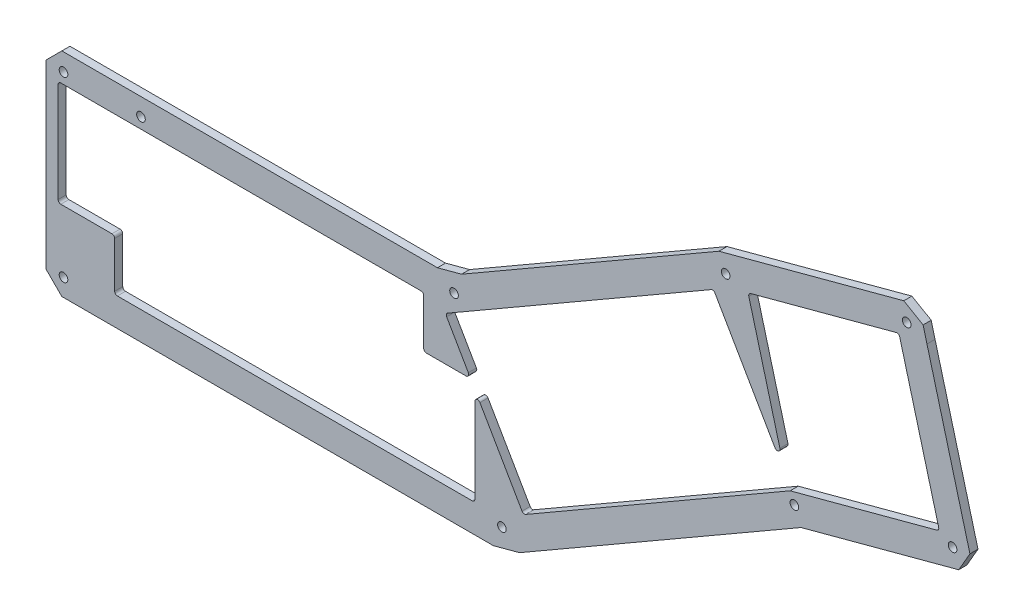
SolidWorks part; units mm, degrees
ref_plane "Plan de face" through (0, 0, 0) normal (0, 0, 1) x (1, 0, 0)
ref_plane "Plan de dessus" through (0, 0, 0) normal (0, 1, 0) x (1, 0, 0)
ref_plane "Plan de droite" through (0, 0, 0) normal (1, 0, 0) x (0, 0, -1)
sketch "Esquisse1" plane through (0, 0, 0) normal (0, 0, 1) x (1, 0, 0)
  line L0 (-73.9886, 18.0851) -> (-59.9886, 18.0851) construction
  line L1 (-73.9886, 37.0851) -> (-59.9886, 37.0851) construction
  line L2 (-73.9886, 37.0851) -> (-73.9886, 23.0851) construction
  line L3 (-73.9886, 23.0851) -> (-59.9886, 23.0851) construction
  line L4 (-59.9886, 37.0851) -> (-59.9886, 23.0851) construction
  line L5 (-73.9886, 18.0851) -> (-73.9886, 4.0851) construction
  line L6 (-73.9886, 4.0851) -> (-59.9886, 4.0851) construction
  line L7 (-59.9886, 18.0851) -> (-59.9886, 4.0851) construction
  line L8 (-73.9886, -0.9149) -> (-59.9886, -0.9149) construction
  line L9 (-73.9886, -0.9149) -> (-73.9886, -14.9149) construction
  line L10 (-73.9886, -14.9149) -> (-59.9886, -14.9149) construction
  line L11 (-59.9886, -0.9149) -> (-59.9886, -14.9149) construction
  line L12 (-73.9886, 37.0851) -> (-73.9886, 18.0851) construction
  line L13 (-54.9886, 18.0851) -> (-40.9886, 18.0851) construction
  line L14 (-54.9886, 37.0851) -> (-40.9886, 37.0851) construction
  line L15 (-54.9886, 37.0851) -> (-54.9886, 23.0851) construction
  line L16 (-54.9886, 23.0851) -> (-40.9886, 23.0851) construction
  line L17 (-40.9886, 37.0851) -> (-40.9886, 23.0851) construction
  line L18 (-54.9886, 18.0851) -> (-54.9886, 4.0851) construction
  line L19 (-54.9886, 4.0851) -> (-40.9886, 4.0851) construction
  line L20 (-40.9886, 18.0851) -> (-40.9886, 4.0851) construction
  line L21 (-54.9886, -0.9149) -> (-40.9886, -0.9149) construction
  line L22 (-54.9886, -0.9149) -> (-54.9886, -14.9149) construction
  line L23 (-54.9886, -14.9149) -> (-40.9886, -14.9149) construction
  line L24 (-40.9886, -0.9149) -> (-40.9886, -14.9149) construction
  line L25 (-54.9886, 37.0851) -> (-54.9886, 18.0851) construction
  line L26 (-35.9886, 18.0851) -> (-21.9886, 18.0851) construction
  line L27 (-35.9886, 37.0851) -> (-21.9886, 37.0851) construction
  line L28 (-35.9886, 37.0851) -> (-35.9886, 23.0851) construction
  line L29 (-35.9886, 23.0851) -> (-21.9886, 23.0851) construction
  line L30 (-21.9886, 37.0851) -> (-21.9886, 23.0851) construction
  line L31 (-35.9886, 18.0851) -> (-35.9886, 4.0851) construction
  line L32 (-35.9886, 4.0851) -> (-21.9886, 4.0851) construction
  line L33 (-21.9886, 18.0851) -> (-21.9886, 4.0851) construction
  line L34 (-35.9886, -0.9149) -> (-21.9886, -0.9149) construction
  line L35 (-35.9886, -0.9149) -> (-35.9886, -14.9149) construction
  line L36 (-35.9886, -14.9149) -> (-21.9886, -14.9149) construction
  line L37 (-21.9886, -0.9149) -> (-21.9886, -14.9149) construction
  line L38 (-35.9886, 37.0851) -> (-35.9886, 18.0851) construction
  line L39 (-16.9886, 18.0851) -> (-2.9886, 18.0851) construction
  line L40 (-16.9886, 37.0851) -> (-2.9886, 37.0851) construction
  line L41 (-16.9886, 37.0851) -> (-16.9886, 23.0851) construction
  line L42 (-16.9886, 23.0851) -> (-2.9886, 23.0851) construction
  line L43 (-2.9886, 37.0851) -> (-2.9886, 23.0851) construction
  line L44 (-16.9886, 18.0851) -> (-16.9886, 4.0851) construction
  line L45 (-16.9886, 4.0851) -> (-2.9886, 4.0851) construction
  line L46 (-2.9886, 18.0851) -> (-2.9886, 4.0851) construction
  line L47 (-16.9886, -0.9149) -> (-2.9886, -0.9149) construction
  line L48 (-16.9886, -0.9149) -> (-16.9886, -14.9149) construction
  line L49 (-16.9886, -14.9149) -> (-2.9886, -14.9149) construction
  line L50 (-2.9886, -0.9149) -> (-2.9886, -14.9149) construction
  line L51 (-16.9886, 37.0851) -> (-16.9886, 18.0851) construction
  line L52 (2.0114, 18.0851) -> (16.0114, 18.0851) construction
  line L53 (2.0114, 37.0851) -> (16.0114, 37.0851) construction
  line L54 (2.0114, 37.0851) -> (2.0114, 23.0851) construction
  line L55 (2.0114, 23.0851) -> (16.0114, 23.0851) construction
  line L56 (16.0114, 37.0851) -> (16.0114, 23.0851) construction
  line L57 (2.0114, 18.0851) -> (2.0114, 4.0851) construction
  line L58 (2.0114, 4.0851) -> (16.0114, 4.0851) construction
  line L59 (16.0114, 18.0851) -> (16.0114, 4.0851) construction
  line L60 (2.0114, -0.9149) -> (16.0114, -0.9149) construction
  line L61 (2.0114, -0.9149) -> (2.0114, -14.9149) construction
  line L62 (2.0114, -14.9149) -> (16.0114, -14.9149) construction
  line L63 (16.0114, -0.9149) -> (16.0114, -14.9149) construction
  line L64 (2.0114, 37.0851) -> (2.0114, 18.0851) construction
  line L65 (21.0114, 18.0851) -> (35.0114, 18.0851) construction
  line L66 (21.0114, 37.0851) -> (35.0114, 37.0851) construction
  line L67 (21.0114, 37.0851) -> (21.0114, 23.0851) construction
  line L68 (21.0114, 23.0851) -> (35.0114, 23.0851) construction
  line L69 (35.0114, 37.0851) -> (35.0114, 23.0851) construction
  line L70 (21.0114, 18.0851) -> (21.0114, 4.0851) construction
  line L71 (21.0114, 4.0851) -> (35.0114, 4.0851) construction
  line L72 (35.0114, 18.0851) -> (35.0114, 4.0851) construction
  line L73 (21.0114, -0.9149) -> (35.0114, -0.9149) construction
  line L74 (21.0114, -0.9149) -> (21.0114, -14.9149) construction
  line L75 (21.0114, -14.9149) -> (35.0114, -14.9149) construction
  line L76 (35.0114, -0.9149) -> (35.0114, -14.9149) construction
  line L77 (21.0114, 37.0851) -> (21.0114, 18.0851) construction
  line L78 (40.0114, 18.0851) -> (54.0114, 18.0851) construction
  line L79 (-97.7538, 39.0851) -> (-97.7538, 2.0851)
  line L80 (-97.7538, 39.0851) -> (-97.7538, 1.0851) construction
  line L81 (-76.7538, 0.0851) -> (-76.7538, -16.9149)
  line L82 (-95.7538, 44.0851) -> (-53.0442, 44.0851) construction
  line L83 (40.0114, 18.0851) -> (40.0114, 4.0851) construction
  line L84 (40.0114, 4.0851) -> (54.0114, 4.0851) construction
  line L85 (54.0114, 18.0851) -> (54.0114, 4.0851) construction
  line L86 (40.0114, -0.9149) -> (54.0114, -0.9149) construction
  line L87 (40.0114, -0.9149) -> (40.0114, -14.9149) construction
  line L88 (40.0114, -14.9149) -> (54.0114, -14.9149) construction
  line L89 (54.0114, -0.9149) -> (54.0114, -14.9149) construction
  line L90 (40.0114, 20.0851) -> (40.0114, 18.0851) construction
  line L91 (-73.9886, 18.0851) -> (-54.9886, 18.0851) construction
  line L92 (56.0114, 20.0851) -> (56.7532, 18.8002) construction
  line L93 (-66.9886, 37.0851) -> (-66.9886, 44.0851) construction
  line L94 (67.3933, 2.371) -> (74.3933, -9.7534) construction
  line L95 (146.1202, 94.012) -> (168.4398, 55.3534)
  line L96 (158.7183, 99.2303) -> (170.2717, 56.1122)
  line L97 (19.0114, 39.0851) -> (37.0114, 39.0851) construction
  line L98 (37.0114, 39.0851) -> (37.0114, 21.0851) construction
  line L99 (19.0114, 21.0851) -> (37.0114, 21.0851) construction
  line L100 (19.0114, 39.0851) -> (19.0114, 21.0851) construction
  line L101 (79.4363, 55.512) -> (88.4363, 39.9235) construction
  line L102 (88.4363, 39.9235) -> (72.8478, 30.9235) construction
  line L103 (63.8478, 46.512) -> (72.8478, 30.9235) construction
  line L104 (79.4363, 55.512) -> (63.8478, 46.512) construction
  line L105 (62.9818, 46.012) -> (71.9818, 30.4235) construction
  line L106 (71.9818, 30.4235) -> (56.3933, 21.4235) construction
  line L107 (47.3933, 37.012) -> (56.3933, 21.4235) construction
  line L108 (62.9818, 46.012) -> (47.3933, 37.012) construction
  line L109 (164.2542, 60.603) -> (148.6657, 51.603) construction
  line L110 (62.2497, 43.2799) -> (71.7497, 26.8254) construction
  line L111 (78.7042, 52.7799) -> (88.2042, 36.3254) construction
  line L112 (95.1587, 62.2799) -> (104.6587, 45.8254) construction
  line L113 (111.6132, 71.7799) -> (121.1132, 55.3254) construction
  line L114 (128.0677, 81.2799) -> (137.5677, 64.8254) construction
  line L115 (144.5221, 90.7799) -> (154.0221, 74.3254) construction
  line L116 (148.6657, 51.603) -> (157.6657, 36.0146) construction
  line L117 (69.1254, 3.371) -> (76.1254, -8.7534) construction
  line L118 (88.2497, -1.7534) -> (76.1254, -8.7534) construction
  line L119 (81.2497, 10.371) -> (88.2497, -1.7534) construction
  line L120 (81.2497, 10.371) -> (69.1254, 3.371) construction
  line L121 (59.6254, 19.8254) -> (66.6254, 7.7011) construction
  line L122 (78.7497, 14.7011) -> (66.6254, 7.7011) construction
  line L123 (71.7497, 26.8254) -> (78.7497, 14.7011) construction
  line L124 (50.1254, 36.2799) -> (57.1254, 24.1556) construction
  line L125 (69.2497, 31.1556) -> (57.1254, 24.1556) construction
  line L126 (62.2497, 43.2799) -> (69.2497, 31.1556) construction
  line L127 (62.2497, 43.2799) -> (50.1254, 36.2799) construction
  line L128 (71.7497, 26.8254) -> (59.6254, 19.8254) construction
  line L129 (85.5799, 12.871) -> (92.5799, 0.7466) construction
  line L130 (104.7042, 7.7466) -> (92.5799, 0.7466) construction
  line L131 (97.7042, 19.871) -> (104.7042, 7.7466) construction
  line L132 (97.7042, 19.871) -> (85.5799, 12.871) construction
  line L133 (76.0799, 29.3254) -> (83.0799, 17.2011) construction
  line L134 (95.2042, 24.2011) -> (83.0799, 17.2011) construction
  line L135 (88.2042, 36.3254) -> (95.2042, 24.2011) construction
  line L136 (66.5799, 45.7799) -> (73.5799, 33.6556) construction
  line L137 (85.7042, 40.6556) -> (73.5799, 33.6556) construction
  line L138 (78.7042, 52.7799) -> (85.7042, 40.6556) construction
  line L139 (78.7042, 52.7799) -> (66.5799, 45.7799) construction
  line L140 (88.2042, 36.3254) -> (76.0799, 29.3254) construction
  line L141 (102.0343, 22.371) -> (109.0343, 10.2466) construction
  line L142 (121.1587, 17.2466) -> (109.0343, 10.2466) construction
  line L143 (114.1587, 29.371) -> (121.1587, 17.2466) construction
  line L144 (114.1587, 29.371) -> (102.0343, 22.371) construction
  line L145 (92.5343, 38.8254) -> (99.5343, 26.7011) construction
  line L146 (111.6587, 33.7011) -> (99.5343, 26.7011) construction
  line L147 (104.6587, 45.8254) -> (111.6587, 33.7011) construction
  line L148 (83.0343, 55.2799) -> (90.0343, 43.1556) construction
  line L149 (102.1587, 50.1556) -> (90.0343, 43.1556) construction
  line L150 (95.1587, 62.2799) -> (102.1587, 50.1556) construction
  line L151 (95.1587, 62.2799) -> (83.0343, 55.2799) construction
  line L152 (104.6587, 45.8254) -> (92.5343, 38.8254) construction
  line L153 (118.4888, 31.871) -> (125.4888, 19.7466) construction
  line L154 (137.6132, 26.7466) -> (125.4888, 19.7466) construction
  line L155 (130.6132, 38.871) -> (137.6132, 26.7466) construction
  line L156 (130.6132, 38.871) -> (118.4888, 31.871) construction
  line L157 (108.9888, 48.3254) -> (115.9888, 36.2011) construction
  line L158 (128.1132, 43.2011) -> (115.9888, 36.2011) construction
  line L159 (121.1132, 55.3254) -> (128.1132, 43.2011) construction
  line L160 (99.4888, 64.7799) -> (106.4888, 52.6556) construction
  line L161 (118.6132, 59.6556) -> (106.4888, 52.6556) construction
  line L162 (111.6132, 71.7799) -> (118.6132, 59.6556) construction
  line L163 (111.6132, 71.7799) -> (99.4888, 64.7799) construction
  line L164 (121.1132, 55.3254) -> (108.9888, 48.3254) construction
  line L165 (134.9433, 41.371) -> (141.9433, 29.2466) construction
  line L166 (154.0677, 36.2466) -> (141.9433, 29.2466) construction
  line L167 (147.0677, 48.371) -> (154.0677, 36.2466) construction
  line L168 (147.0677, 48.371) -> (134.9433, 41.371) construction
  line L169 (125.4433, 57.8254) -> (132.4433, 45.7011) construction
  line L170 (144.5677, 52.7011) -> (132.4433, 45.7011) construction
  line L171 (137.5677, 64.8254) -> (144.5677, 52.7011) construction
  line L172 (115.9433, 74.2799) -> (122.9433, 62.1556) construction
  line L173 (135.0677, 69.1556) -> (122.9433, 62.1556) construction
  line L174 (128.0677, 81.2799) -> (135.0677, 69.1556) construction
  line L175 (128.0677, 81.2799) -> (115.9433, 74.2799) construction
  line L176 (137.5677, 64.8254) -> (125.4433, 57.8254) construction
  line L177 (151.3978, 50.871) -> (158.3978, 38.7466) construction
  line L178 (170.5221, 45.7466) -> (158.3978, 38.7466) construction
  line L179 (163.5221, 57.871) -> (170.5221, 45.7466) construction
  line L180 (163.5221, 57.871) -> (151.3978, 50.871) construction
  line L181 (141.8978, 67.3254) -> (148.8978, 55.2011) construction
  line L182 (161.0221, 62.2011) -> (148.8978, 55.2011) construction
  line L183 (154.0221, 74.3254) -> (161.0221, 62.2011) construction
  line L184 (132.3978, 83.7799) -> (139.3978, 71.6556) construction
  line L185 (151.5221, 78.6556) -> (139.3978, 71.6556) construction
  line L186 (144.5221, 90.7799) -> (151.5221, 78.6556) construction
  line L187 (144.5221, 90.7799) -> (132.3978, 83.7799) construction
  line L188 (154.0221, 74.3254) -> (141.8978, 67.3254) construction
  line L189 (173.2542, 45.0146) -> (157.6657, 36.0146) construction
  line L190 (164.2542, 60.603) -> (173.2542, 45.0146) construction
  line L191 (178.3169, 34.0986) -> (169.0534, 56.4627) construction
  line L192 (169.5193, 62.7839) -> (174.1781, 45.3972) construction
  line L193 (174.1781, 45.3972) -> (191.5647, 50.056) construction
  line L194 (186.906, 67.4426) -> (191.5647, 50.056) construction
  line L195 (162.1337, 98.0749) -> (167.0513, 79.7223) construction
  line L196 (169.5193, 62.7839) -> (186.906, 67.4426) construction
  line L197 (167.0513, 79.7223) -> (180.5742, 83.3457) construction
  line L198 (162.1337, 98.0749) -> (175.6567, 101.6983) construction
  line L199 (162.1337, 98.0749) -> (165.7572, 84.5519) construction
  line L200 (165.7572, 84.5519) -> (179.2801, 88.1754) construction
  line L201 (175.6567, 101.6983) -> (179.2801, 88.1754) construction
  line L202 (167.0513, 79.7223) -> (170.6747, 66.1993) construction
  line L203 (170.6747, 66.1993) -> (184.1977, 69.8228) construction
  line L204 (180.5742, 83.3457) -> (184.1977, 69.8228) construction
  line L205 (171.9688, 61.3697) -> (185.4918, 64.9932) construction
  line L206 (171.9688, 61.3697) -> (175.5923, 47.8467) construction
  line L207 (175.5923, 47.8467) -> (189.1152, 51.4702) construction
  line L208 (185.4918, 64.9932) -> (189.1152, 51.4702) construction
  line L209 (185.4038, 84.6398) -> (198.9268, 88.2633) construction
  line L210 (180.4863, 102.9924) -> (194.0092, 106.6159) construction
  line L211 (180.4863, 102.9924) -> (184.1097, 89.4695) construction
  line L212 (184.1097, 89.4695) -> (197.6327, 93.0929) construction
  line L213 (194.0092, 106.6159) -> (197.6327, 93.0929) construction
  line L214 (185.4038, 84.6398) -> (189.0273, 71.1169) construction
  line L215 (189.0273, 71.1169) -> (202.5503, 74.7403) construction
  line L216 (198.9268, 88.2633) -> (202.5503, 74.7403) construction
  line L217 (190.3214, 66.2873) -> (203.8444, 69.9107) construction
  line L218 (190.3214, 66.2873) -> (193.9449, 52.7643) construction
  line L219 (193.9449, 52.7643) -> (207.4678, 56.3878) construction
  line L220 (203.8444, 69.9107) -> (207.4678, 56.3878) construction
  line L221 (187.8719, 67.7015) -> (192.5307, 50.3148) construction
  line L222 (192.5307, 50.3148) -> (209.9173, 54.9735) construction
  line L223 (205.2586, 72.3602) -> (209.9173, 54.9735) construction
  line L224 (180.4863, 102.9924) -> (185.4038, 84.6398) construction
  line L225 (187.8719, 67.7015) -> (205.2586, 72.3602) construction
  line L226 (203.7564, 89.5574) -> (217.2794, 93.1809) construction
  line L227 (198.8389, 107.91) -> (212.3618, 111.5335) construction
  line L228 (198.8389, 107.91) -> (202.4623, 94.387) construction
  line L229 (202.4623, 94.387) -> (215.9853, 98.0105) construction
  line L230 (212.3618, 111.5335) -> (215.9853, 98.0105) construction
  line L231 (203.7564, 89.5574) -> (207.3799, 76.0344) construction
  line L232 (207.3799, 76.0344) -> (220.9029, 79.6579) construction
  line L233 (217.2794, 93.1809) -> (220.9029, 79.6579) construction
  line L234 (208.674, 71.2048) -> (222.197, 74.8283) construction
  line L235 (208.674, 71.2048) -> (212.2975, 57.6819) construction
  line L236 (212.2975, 57.6819) -> (225.8204, 61.3053) construction
  line L237 (222.197, 74.8283) -> (225.8204, 61.3053) construction
  line L238 (206.2245, 72.619) -> (210.8833, 55.2324) construction
  line L239 (210.8833, 55.2324) -> (228.2699, 59.8911) construction
  line L240 (223.6112, 77.2778) -> (228.2699, 59.8911) construction
  line L241 (198.8389, 107.91) -> (203.7564, 89.5574) construction
  line L242 (206.2245, 72.619) -> (223.6112, 77.2778) construction
  line L243 (167.0513, 79.7223) -> (185.4038, 84.6398) construction
  line L244 (38.0114, 20.0851) -> (56.0114, 20.0851) construction
  line L245 (56.0114, 20.0851) -> (56.0114, 2.0851) construction
  line L246 (38.0114, 2.0851) -> (56.0114, 2.0851) construction
  line L247 (38.0114, 20.0851) -> (38.0114, 2.0851) construction
  line L248 (72.4818, 29.5575) -> (56.8933, 20.5575) construction
  line L249 (56.8933, 20.5575) -> (65.8933, 4.969) construction
  line L250 (81.4818, 13.969) -> (65.8933, 4.969) construction
  line L251 (72.4818, 29.5575) -> (81.4818, 13.969) construction
  line L252 (56.8933, 20.5575) -> (57.6111, 19.3142) construction
  line L253 (164.6018, 81.1365) -> (169.2605, 63.7498) construction
  line L254 (169.2605, 63.7498) -> (186.6472, 68.4086) construction
  line L255 (181.9884, 85.7952) -> (186.6472, 68.4086) construction
  line L256 (164.6018, 81.1365) -> (181.9884, 85.7952) construction
  line L257 (154.7542, 77.0575) -> (163.7542, 61.469) construction
  line L258 (163.7542, 61.469) -> (148.1657, 52.469) construction
  line L259 (139.1657, 68.0575) -> (148.1657, 52.469) construction
  line L260 (154.7542, 77.0575) -> (139.1657, 68.0575) construction
  line L261 (196.3894, 109.3242) -> (213.776, 113.983) construction
  line L262 (-94.7538, 35.7952) -> (-76.7538, 35.7952) construction
  line L263 (-94.7538, 35.7952) -> (-94.7538, 2.7952) construction
  line L264 (-94.7538, 2.7952) -> (-76.7538, 2.7952) construction
  line L265 (-76.7538, 35.7952) -> (-76.7538, 2.7952) construction
  line L266 (213.776, 113.983) -> (218.4348, 96.5963) construction
  line L267 (201.0481, 91.9375) -> (218.4348, 96.5963) construction
  line L268 (196.3894, 109.3242) -> (201.0481, 91.9375) construction
  line L269 (-75.9886, -16.9149) -> (-57.9886, -16.9149) construction
  line L270 (-57.9886, 1.0851) -> (-57.9886, -16.9149) construction
  line L271 (-75.9886, 1.0851) -> (-57.9886, 1.0851) construction
  line L272 (-75.9886, 1.0851) -> (-75.9886, -16.9149) construction
  line L273 (38.0114, -16.9149) -> (56.0114, -16.9149) construction
  line L274 (56.0114, 1.0851) -> (56.0114, -16.9149) construction
  line L275 (38.0114, 1.0851) -> (56.0114, 1.0851) construction
  line L276 (38.0114, 1.0851) -> (38.0114, -16.9149) construction
  line L277 (-75.9886, 39.0851) -> (-57.9886, 39.0851) construction
  line L278 (-57.9886, 39.0851) -> (-57.9886, 21.0851) construction
  line L279 (-75.9886, 21.0851) -> (-57.9886, 21.0851) construction
  line L280 (-75.9886, 39.0851) -> (-75.9886, 21.0851) construction
  line L281 (145.2542, 93.512) -> (129.6657, 84.512) construction
  line L282 (129.6657, 84.512) -> (138.6657, 68.9235) construction
  line L283 (154.2542, 77.9235) -> (138.6657, 68.9235) construction
  line L284 (145.2542, 93.512) -> (154.2542, 77.9235) construction
  line L285 (223.4353, 116.5711) -> (228.0941, 99.1845) construction
  line L286 (148.2159, 106.7689) -> (211.1879, 123.6422) construction
  line L287 (177.5508, 35.9482) -> (235.6877, 51.5259) construction
  line L288 (177.5508, 35.9482) -> (72.9989, -24.4149) construction
  line L289 (-95.7538, -26.9149) -> (63.6687, -26.9149) construction
  line L290 (-100.7538, 35.7952) -> (-100.7538, -21.9149) construction
  line L291 (-75.9886, 49.0851) -> (43.3046, 49.0851) construction
  line L292 (148.2159, 106.7689) -> (52.6347, 51.5851) construction
  line L293 (-75.9886, 49.0851) -> (-57.9886, 49.0851) construction
  line L294 (140.2542, 102.1722) -> (124.6657, 93.1722) construction
  line L295 (193.8012, 118.9835) -> (211.1879, 123.6422) construction
  line L296 (213.4714, 45.5731) -> (230.8581, 50.2318) construction
  line L297 (38.0114, -26.9149) -> (38.0114, -85.4624) construction
  line L298 (178.2542, 36.3543) -> (162.6657, 27.3543) construction
  line L299 (38.0114, -26.9149) -> (56.0114, -26.9149) construction
  line L300 (-100.7538, 2.7952) -> (-100.7538, -38.0419) construction
  line L301 (-100.7538, 35.7952) -> (-100.7538, 2.7952) construction
  line L302 (-75.9886, 49.0851) -> (-95.7538, 49.0851) construction
  line L303 (-100.7538, 44.0851) -> (-100.7538, 35.7952) construction
  line L304 (211.1879, 123.6422) -> (216.0732, 124.9512) construction
  line L305 (222.1691, 121.4083) -> (223.4353, 116.5711) construction
  line L306 (228.0941, 99.1845) -> (239.2233, 57.6497) construction
  line L307 (216.0732, 124.9512) -> (222.1691, 121.4083) construction
  line L308 (235.6877, 51.5259) -> (239.2233, 57.6497) construction
  line L309 (63.6687, -26.9149) -> (72.9989, -24.4149) construction
  line L310 (52.6347, 51.5851) -> (43.3046, 49.0851) construction
  line L311 (-95.7538, 49.0851) -> (-100.7538, 44.0851) construction
  line L312 (-100.7538, -21.9149) -> (-95.7538, -26.9149) construction
  line L313 (-95.7538, 49.0851) -> (-95.7538, 44.0851) construction
  line L314 (-95.7538, 44.0851) -> (-100.7538, 44.0851) construction
  line L315 (-95.7538, -26.9149) -> (-95.7538, -21.9149) construction
  line L316 (68.3338, -25.6649) -> (67.0397, -20.8353) construction
  line L317 (47.9697, 50.3351) -> (49.2637, 45.5055) construction
  line L318 (177.5508, 35.9482) -> (175.6374, 40.5676) construction
  line L319 (148.2159, 106.7689) -> (150.1293, 102.1495) construction
  line L320 (239.2233, 57.6497) -> (234.3936, 56.3556) construction
  line L321 (216.0732, 124.9512) -> (217.3634, 120.1206) construction
  line L322 (146.1202, 94.012) -> (155.1202, 78.4235) construction
  line L323 (-76.7538, 35.7952) -> (-96.7538, 35.7952) construction
  line L324 (148.6019, 105.8371) -> (53.0207, 50.6533) construction
  line L325 (163.6358, 80.8777) -> (168.2946, 63.491) construction
  line L326 (57.0114, 14.621) -> (57.0114, -16.9149)
  line L327 (-77.7538, 1.0851) -> (-96.7538, 1.0851)
  line L328 (-96.7538, 39.0851) -> (-96.7538, 1.0851) construction
  line L329 (53.0207, 50.6533) -> (43.4362, 48.0851) construction
  line L330 (-75.9886, 48.0851) -> (43.4362, 48.0851) construction
  line L331 (-75.9886, 48.0851) -> (-95.3395, 48.0851) construction
  line L332 (-95.3395, 48.0851) -> (-99.7538, 43.6709) construction
  line L333 (-99.7538, 43.6709) -> (-99.7538, 35.7952) construction
  line L334 (-99.7538, 35.7952) -> (-99.7538, -21.5007) construction
  line L335 (-99.7538, -21.5007) -> (-95.3395, -25.9149) construction
  line L336 (-95.3395, -25.9149) -> (63.5371, -25.9149) construction
  line L337 (63.5371, -25.9149) -> (72.6129, -23.483) construction
  line L338 (177.1648, 36.88) -> (72.6129, -23.483) construction
  line L339 (177.1648, 36.88) -> (235.0288, 52.3847) construction
  line L340 (235.0288, 52.3847) -> (238.1501, 57.7909) construction
  line L341 (227.1281, 98.9257) -> (238.1501, 57.7909) construction
  line L342 (222.4686, 116.3151) -> (227.1281, 98.9257) construction
  line L343 (221.307, 120.7527) -> (222.4686, 116.3151) construction
  line L344 (215.9303, 123.8777) -> (221.307, 120.7527) construction
  line L345 (211.4467, 122.6763) -> (215.9303, 123.8777) construction
  line L346 (148.6019, 105.8371) -> (211.4467, 122.6763) construction
  line L347 (214.742, 114.2418) -> (229.2358, 60.1499)
  line L348 (174.0769, 44.3349) -> (228.5287, 58.9252)
  line L349 (174.0769, 44.3349) -> (75.8933, -12.3515)
  line L350 (159.4254, 100.455) -> (213.5172, 114.9489)
  line L351 (144.7542, 94.378) -> (46.8933, 37.878)
  line L352 (-75.7538, -17.9149) -> (56.0114, -17.9149)
  line L353 (-96.7538, 40.0851) -> (37.0114, 40.0851)
  line L354 (2.0114, 40.0851) -> (16.0114, 40.0851) construction
  line L355 (126.5677, 83.878) -> (114.4433, 76.878) construction
  line L356 (179.7098, 105.8902) -> (193.2328, 109.5137) construction
  line L357 (215.2596, 112.3099) -> (218.8831, 98.787) construction
  line L358 (194.7213, 49.8665) -> (208.2443, 53.49) construction
  line L359 (155.5677, 33.6485) -> (143.4433, 26.6485) construction
  line L360 (40.0114, -17.9149) -> (54.0114, -17.9149) construction
  line L361 (58.8774, 15.121) -> (74.5273, -11.9854)
  line L362 (66.5273, 1.871) -> (73.5273, -10.2534) construction
  line L363 (40.0114, 37.0851) -> (40.0114, 23.0851) construction
  line L364 (57.0114, 1.0851) -> (57.0114, -16.9149) construction
  line L365 (46.5273, 36.512) -> (54.568, 22.5851)
  line L366 (51.52, 37.0851) -> (54.0114, 37.0851) construction
  line L367 (40.0114, 23.0851) -> (54.0114, 23.0851) construction
  line L368 (39.0114, 21.0851) -> (53.702, 21.0851)
  line L369 (54.0114, 29.5492) -> (54.0114, 25.5492) construction
  line L370 (38.0114, 39.0851) -> (38.0114, 22.0851)
  line L371 (38.0114, 39.0851) -> (38.0114, 21.0851) construction
  line L372 (46.5273, 36.512) -> (55.5273, 20.9235) construction
  line L373 (-75.9886, 48.5851) -> (43.3704, 48.5851) construction
  line L374 (38.0114, 21.0851) -> (56.0114, 21.0851) construction
  line L375 (52.8277, 51.1192) -> (43.3704, 48.5851) construction
  line L376 (148.4089, 106.303) -> (52.8277, 51.1192) construction
  line L377 (148.4089, 106.303) -> (211.3173, 123.1592) construction
  line L378 (211.3173, 123.1592) -> (216.0018, 124.4145) construction
  line L379 (216.0018, 124.4145) -> (221.738, 121.0805) construction
  line L380 (221.738, 121.0805) -> (222.952, 116.4431) construction
  line L381 (222.952, 116.4431) -> (227.6111, 99.0551) construction
  line L382 (227.6111, 99.0551) -> (238.6867, 57.7203) construction
  line L383 (235.3583, 51.9553) -> (238.6867, 57.7203) construction
  line L384 (177.3578, 36.4141) -> (235.3583, 51.9553) construction
  line L385 (177.3578, 36.4141) -> (72.8059, -23.949) construction
  line L386 (63.6029, -26.4149) -> (72.8059, -23.949) construction
  line L387 (-95.5467, -26.4149) -> (63.6029, -26.4149) construction
  line L388 (-100.2538, -21.7078) -> (-95.5467, -26.4149) construction
  line L389 (-100.2538, 35.7952) -> (-100.2538, -21.7078) construction
  line L390 (-100.2538, 43.878) -> (-100.2538, 35.7952) construction
  line L391 (-95.5467, 48.5851) -> (-100.2538, 43.878) construction
  line L392 (-75.9886, 48.5851) -> (-95.5467, 48.5851) construction
  line L393 (-75.9886, 49.5851) -> (43.2388, 49.5851) construction
  line L394 (52.4417, 52.051) -> (43.2388, 49.5851) construction
  line L395 (148.0229, 107.2348) -> (52.4417, 52.051) construction
  line L396 (148.0229, 107.2348) -> (211.0584, 124.1252) construction
  line L397 (211.0584, 124.1252) -> (216.1447, 125.488) construction
  line L398 (216.1447, 125.488) -> (222.6001, 121.7361) construction
  line L399 (222.6001, 121.7361) -> (223.9186, 116.6992) construction
  line L400 (223.9186, 116.6992) -> (228.577, 99.3139) construction
  line L401 (228.577, 99.3139) -> (239.7598, 57.579) construction
  line L402 (236.0172, 51.0966) -> (239.7598, 57.579) construction
  line L403 (177.7438, 35.4823) -> (236.0172, 51.0966) construction
  line L404 (177.7438, 35.4823) -> (73.1918, -24.8808) construction
  line L405 (63.7346, -27.4149) -> (73.1918, -24.8808) construction
  line L406 (-95.9609, -27.4149) -> (63.7346, -27.4149) construction
  line L407 (-101.2538, -22.122) -> (-95.9609, -27.4149) construction
  line L408 (-101.2538, 35.7952) -> (-101.2538, -22.122) construction
  line L409 (-101.2538, 44.2922) -> (-101.2538, 35.7952) construction
  line L410 (-95.9609, 49.5851) -> (-101.2538, 44.2922) construction
  line L411 (-75.9886, 49.5851) -> (-95.9609, 49.5851) construction
  line L412 (-75.9886, 50.5851) -> (-96.3751, 50.5851)
  line L413 (-96.3751, 50.5851) -> (-102.2538, 44.7064)
  line L414 (-102.2538, 44.7064) -> (-102.2538, 35.7952)
  line L415 (-102.2538, 35.7952) -> (-102.2538, -22.5362)
  line L416 (-102.2538, -22.5362) -> (-96.3751, -28.4149)
  line L417 (-96.3751, -28.4149) -> (63.8662, -28.4149)
  line L418 (63.8662, -28.4149) -> (73.5778, -25.8127)
  line L419 (178.1298, 34.5504) -> (73.5778, -25.8127)
  line L420 (178.1298, 34.5504) -> (236.6761, 50.2379)
  line L421 (236.6761, 50.2379) -> (240.833, 57.4377)
  line L422 (229.5429, 99.5727) -> (240.833, 57.4377)
  line L423 (224.8853, 116.9552) -> (229.5429, 99.5727)
  line L424 (223.4622, 122.3917) -> (224.8853, 116.9552)
  line L425 (216.2876, 126.5616) -> (223.4622, 122.3917)
  line L426 (210.7996, 125.0911) -> (216.2876, 126.5616)
  line L427 (147.6369, 108.1667) -> (210.7996, 125.0911)
  line L428 (147.6369, 108.1667) -> (52.0557, 52.9829)
  line L429 (52.0557, 52.9829) -> (43.1071, 50.5851)
  line L430 (-75.9886, 50.5851) -> (43.1071, 50.5851)
  circle A0 centre (-95.7538, 44.0851) radius 1.5 construction
  circle A1 centre (-95.7538, -21.9149) radius 1.5 construction
  circle A2 centre (67.0397, -20.8353) radius 1.5 construction
  circle A3 centre (49.2637, 45.5055) radius 1.5 construction
  circle A4 centre (175.6374, 40.5676) radius 1.5 construction
  circle A5 centre (150.1293, 102.1495) radius 1.5 construction
  circle A6 centre (234.3936, 56.3556) radius 1.5 construction
  circle A7 centre (217.3634, 120.1206) radius 1.5 construction
  circle A8 centre (-66.9886, 44.0851) radius 1.5 construction
  arc A9 (168.4398, 55.3534) -> (170.2717, 56.1122) centre (169.3058, 55.8534) ccw
  arc A10 (57.0114, 14.621) -> (58.8774, 15.121) centre (58.0114, 14.621) cw
  arc A11 (53.702, 21.0851) -> (54.568, 22.5851) centre (53.702, 22.0851) ccw
  arc A12 (39.0114, 21.0851) -> (38.0114, 22.0851) centre (39.0114, 22.0851) cw
  arc A13 (-97.7538, 39.0851) -> (-96.7538, 40.0851) centre (-96.7538, 39.0851) cw
  arc A14 (-96.7538, 1.0851) -> (-97.7538, 2.0851) centre (-96.7538, 2.0851) cw
  arc A15 (-76.7538, 0.0851) -> (-77.7538, 1.0851) centre (-77.7538, 0.0851) ccw
  arc A16 (-76.7538, -16.9149) -> (-75.7538, -17.9149) centre (-75.7538, -16.9149) ccw
  arc A17 (228.5287, 58.9252) -> (229.2358, 60.1499) centre (228.2699, 59.8911) ccw
  arc A18 (214.742, 114.2418) -> (213.5172, 114.9489) centre (213.776, 113.983) ccw
  arc A19 (158.7183, 99.2303) -> (159.4254, 100.455) centre (159.6842, 99.4891) cw
  arc A20 (146.1202, 94.012) -> (144.7542, 94.378) centre (145.2542, 93.512) ccw
  arc A21 (57.0114, -16.9149) -> (56.0114, -17.9149) centre (56.0114, -16.9149) cw
  arc A22 (74.5273, -11.9854) -> (75.8933, -12.3515) centre (75.3933, -11.4854) ccw
  arc A23 (46.5273, 36.512) -> (46.8933, 37.878) centre (47.3933, 37.012) cw
  arc A24 (38.0114, 39.0851) -> (37.0114, 40.0851) centre (37.0114, 39.0851) ccw
  circle A25 centre (-95.7538, 44.0851) radius 1.6
  circle A26 centre (-66.9886, 44.0851) radius 1.6
  circle A27 centre (-95.7538, -21.9149) radius 1.6
  circle A28 centre (49.2637, 45.5055) radius 1.6
  circle A29 centre (67.0397, -20.8353) radius 1.6
  circle A30 centre (175.6374, 40.5676) radius 1.6
  circle A31 centre (234.3936, 56.3556) radius 1.6
  circle A32 centre (217.3634, 120.1206) radius 1.6
  circle A33 centre (150.1293, 102.1495) radius 1.6
  point P85 (40.0114, 37.0851)
  point P86 (54.0114, 23.0851)
  point P88 (54.0114, 37.0851)
  point P102 (38.0114, 39.0851)
  point P103 (56.0114, 39.0851)
  point P304 (48.3046, 49.0851)
  point P305 (240.5174, 52.82)
  point P308 (68.6687, -26.9149)
  point P309 (-100.7538, -26.9149)
  point P311 (-100.7538, 49.0851)
  point P312 (220.9029, 126.2453)
  point P409 (172.2377, 48.7752)
  dimension "D32" = 3
  dimension "D33" = 5
  dimension "D40" = 5
  dimension "D41" = 5
  dimension "D42" = 5
  dimension "D43" = 5
  dimension "D44" = 20
  dimension "D53" = 2
  dimension "D56" = 1
  dimension "D59" = 1
  dimension "D63" = 1
  dimension "D64" = 1
  dimension "D65" = 1
  dimension "D1" = 14
  dimension "D2" = 14
  dimension "D4" = 19
  dimension "D6" = 19
  dimension "D7" = 30
  dimension "D10" = 1
  dimension "D11" = 2
  dimension "D13" = 0.5
  dimension "D15" = 2
  dimension "D12" = 7.5
  dimension "D14" = 19
  dimension "D18" = 2
  dimension "D20" = 18
  dimension "D21" = 33
  dimension "D22" = 2
  dimension "D8" = 1
  dimension "D9" = 2
  dimension "D16" = 2
  dimension "D19" = 2
  dimension "D23" = 2
  dimension "D24" = 10
  dimension "D25" = 10
  dimension "D26" = 10
  dimension "D27" = 10
  dimension "D28" = 10
  dimension "D29" = 6
  dimension "D30" = 10
  dimension "D31" = 10
  dimension "D45" = 1
  dimension "D46" = 3
  dimension "D47" = 3
  dimension "D48" = 3
  dimension "D49" = 3
  dimension "D50" = 3
  dimension "D51" = 3
  dimension "D52" = 3
  dimension "D54" = 1
  dimension "D55" = 1
  dimension "D57" = 1
  dimension "D58" = 1
  dimension "D60" = 1
  dimension "D61" = 1
  dimension "D62" = 1
  dimension "D66" = 0.5
  dimension "D67" = 1
  dimension "D68" = 1
  dimension "D69" = 0.1
  dimension "D3" = 3
  dimension "D5" = 7
  dimension "D17" = 3
extrude "Boss.-Extru.1" add sketch "Esquisse1" along normal blind 3
